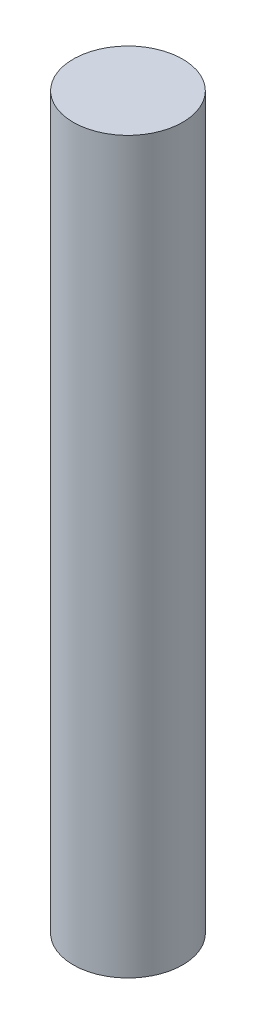
SolidWorks part; units mm, degrees
ref_plane "Спереди" through (0, 0, 0) normal (0, 0, 1) x (1, 0, 0)
ref_plane "Сверху" through (0, 0, 0) normal (0, 1, 0) x (1, 0, 0)
ref_plane "Справа" through (0, 0, 0) normal (1, 0, 0) x (0, 0, -1)
sketch "Эскиз1" plane through (0, 0, 0) normal (0, 1, 0) x (1, 0, 0)
  circle A0 centre (0, 0) radius 1.5
  dimension "D1" = 3
extrude "Бобышка-Вытянуть1" add sketch "Эскиз1" along normal blind 20
